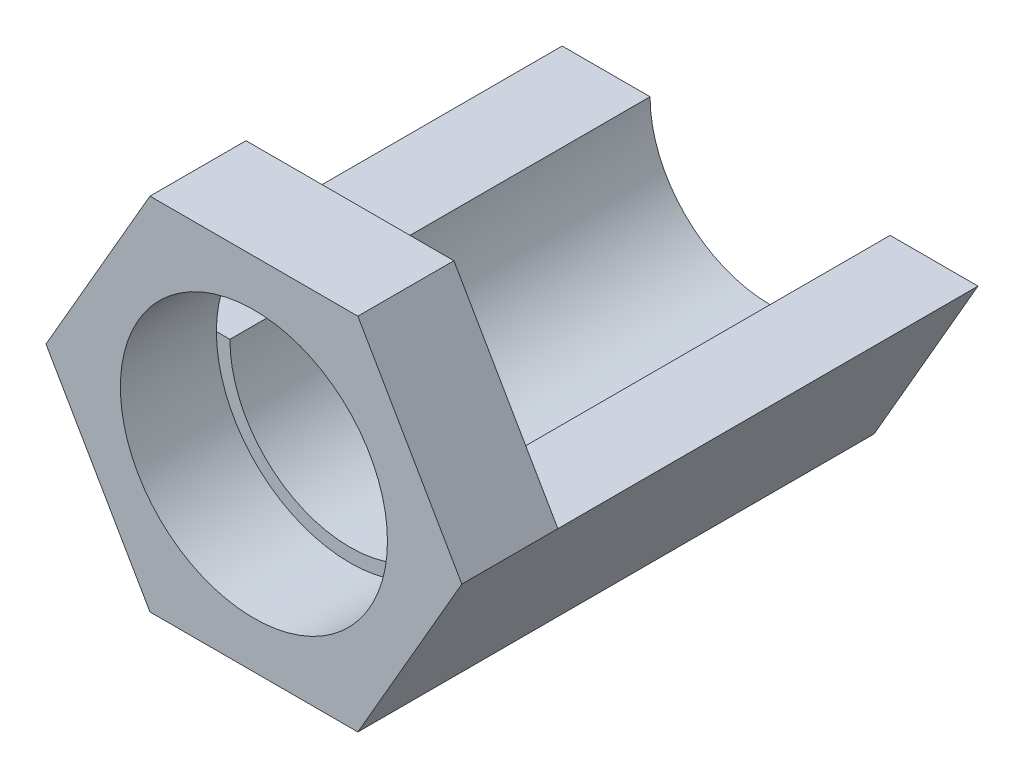
SolidWorks part; units mm, degrees
ref_plane "Front Plane" through (0, 0, 0) normal (0, 0, 1) x (1, 0, 0)
ref_plane "Top Plane" through (0, 0, 0) normal (0, 1, 0) x (1, 0, 0)
ref_plane "Right Plane" through (0, 0, 0) normal (1, 0, 0) x (0, 0, -1)
sketch "Sketch1" plane through (0, 0, 0) normal (0, 0, 1) x (1, 0, 0)
  line L1 (17.3205, 0) -> (8.6603, 15)
  line L2 (8.6603, 15) -> (-8.6603, 15)
  line L3 (-8.6603, 15) -> (-17.3205, 0)
  line L4 (-17.3205, 0) -> (-8.6603, -15)
  line L5 (-8.6603, -15) -> (8.6603, -15)
  line L6 (8.6603, -15) -> (17.3205, 0)
  circle A0 centre (0, 0) radius 11.125
  circle A2 centre (0, 0) radius 15 construction
  dimension "D1" = 22.25
  dimension "D2" = 30
extrude "Boss-Extrude1" add sketch "Sketch1" against normal blind 8 contours A0
sketch "Sketch2" plane through (0, 0, -8) normal (0, 0, -1) x (-1, 0, 0)
  line L2 (-17.3205, 0) -> (-10, 0)
  line L4 (-17.3205, 0) -> (-8.6603, -15)
  line L5 (-8.6603, -15) -> (8.6603, -15)
  line L6 (8.6603, -15) -> (17.3205, 0)
  line L9 (17.3205, 0) -> (10, 0)
  line L10 (-8.6603, -15) -> (-17.3205, 0) construction
  line L11 (8.8592, 14.6554) -> (3.9157, 23.2179) [skipped]
  line L12 (12.2293, 15) -> (-7.545, 15) [skipped]
  line L13 (-17.1215, 0.3446) -> (-22.0651, -8.2179) [skipped]
  arc A1 (-10, 0) -> (10, 0) centre (0, 0) ccw
  arc A2 (-17.125, 0) -> (17.125, 0) centre (0, 0) ccw construction
  dimension "D1" = 20
  dimension "D2" = 17.125
extrude "Boss-Extrude2" add sketch "Sketch2" along normal blind 35
